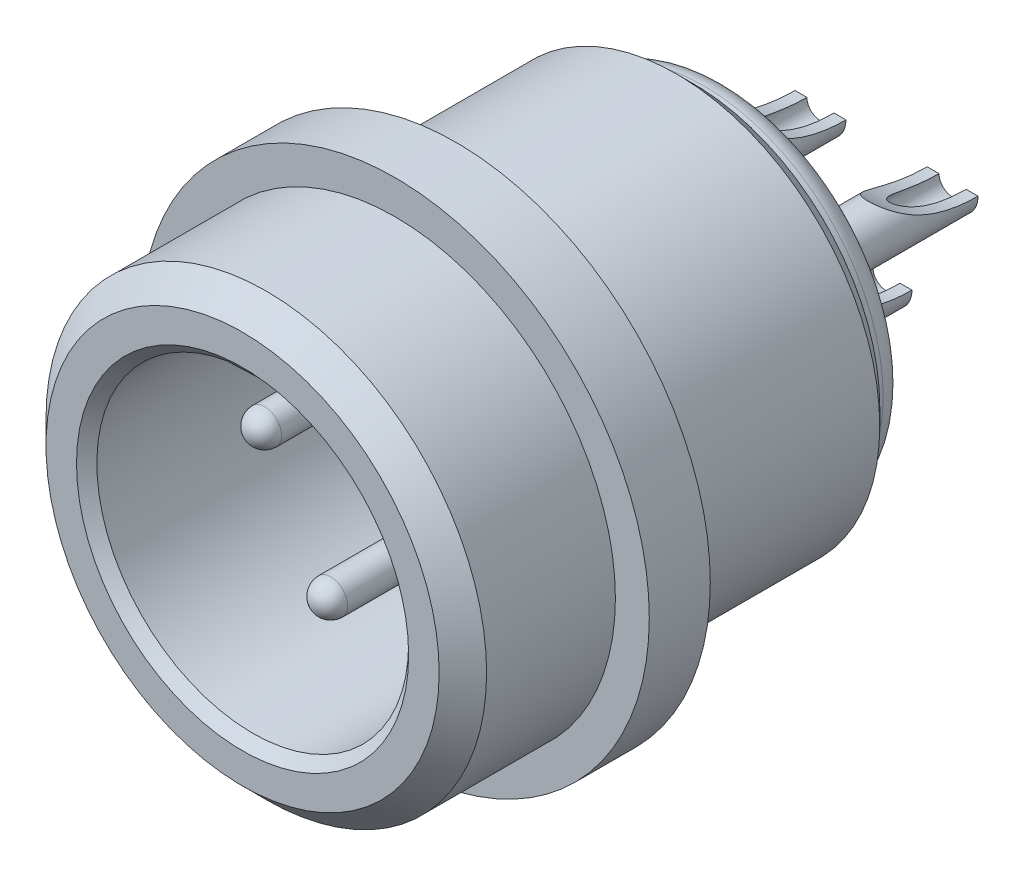
SolidWorks part; units mm, degrees
ref_plane "Спереди" through (0, 0, 0) normal (0, 0, 1) x (1, 0, 0)
ref_plane "Сверху" through (0, 0, 0) normal (0, 1, 0) x (1, 0, 0)
ref_plane "Справа" through (0, 0, 0) normal (1, 0, 0) x (0, 0, -1)
sketch "Эскиз1" plane through (0, 0, 0) normal (1, 0, 0) x (0, 0, -1)
  line L0 (0, 0) -> (112.3363, 0) construction
  line L1 (0, 4.6) -> (0, 5.8)
  line L2 (0.7, 6.5) -> (4.5, 6.5)
  line L3 (4.5, 6.5) -> (4.5, 7.5)
  line L4 (4.5, 7.5) -> (6.3, 7.5)
  line L5 (6.3, 7.5) -> (6.3, 6)
  line L6 (13.3, 5.3) -> (13.6, 5.3)
  line L7 (14.3, 4.6) -> (14.3, 4.5)
  line L8 (14.3, 4.5) -> (14, 4.5)
  line L9 (14, 4.5) -> (14, 0)
  line L10 (6.3, 6) -> (12.8, 6)
  line L11 (13.3, 5.5) -> (13.3, 5.3)
  line L12 (0, 4.6) -> (8.7, 4.6)
  line L13 (8.7, 4.6) -> (8.7, 0)
  line L14 (14, 0) -> (8.7, 0)
  line L15 (0, 5.8) -> (0.7, 6.5)
  line L16 (12.8, 6) -> (13.3, 5.5)
  arc A0 (14.3, 4.6) -> (13.6, 5.3) centre (13.6, 4.6) ccw
  point P4 (0, 6.5)
  point P15 (14.3, 5.3)
  point P19 (13.3, 6)
  dimension "D11" = 0.7
  dimension "D2" = 9.2
  dimension "D3" = 13
  dimension "D4" = 4.5
  dimension "D5" = 15
  dimension "D6" = 1.8
  dimension "D7" = 10.6
  dimension "D8" = 9
  dimension "D9" = 14.3
  dimension "D10" = 0.3
  dimension "D12" = 7
  dimension "D13" = 12
  dimension "D14" = 8.7
revolve "Повернуть1" add sketch "Эскиз1" angle 360 about L0
cosmetic thread "Условное изображение резьбы1" parameters "D2"=12
cosmetic thread "Условное изображение резьбы2" parameters "D2"=11
sketch "Эскиз2" plane through (0, 0, -8.7) normal (0, 0, 1) x (1, 0, 0)
  line L0 (-5.6904, 0) -> (5.786, 0) construction
  line L1 (0, 0) -> (0, -4.6) construction
  line L2 (0, 0) -> (1.9486, 1.125) construction
  line L3 (0, 0) -> (-1.9486, 1.125) construction
  circle A0 centre (1.9486, 1.125) radius 0.5
  circle A1 centre (0, -2.25) radius 0.5
  circle A2 centre (0, 0) radius 2.25 construction
  circle A3 centre (-1.9486, 1.125) radius 0.5
  circle A4 centre (0, 0) radius 4.6 construction
  circle A5 centre (0, 0) radius 4.6 construction
  dimension "D1" = 1
  dimension "D2" = 1
  dimension "D3" = 120
  dimension "D4" = 4.5
  dimension "D5" = 1
  dimension "D6" = 120
extrude "Вытянуть1" add sketch "Эскиз2" along normal offset from surface 2.1 and the other way blind 6 up to face at (4.6, 0, 0)
sketch "Эскиз8" plane through (0, 0, -8.7) normal (0, 0, 1) x (1, 0, 0)
  line L0 (0, 0) -> (0, 4.6) construction
  circle A1 centre (0, 4.6) radius 0.75
  circle A2 centre (0, 0) radius 4.6 construction
  dimension "D1" = 1.5
extrude "Бобышка-Вытянуть1" add sketch "Эскиз8" along normal up to surface (8.7 mm away) up to face at (4.6, 0, 0)
fillet "Скругление1" radius 0.5 3 edges at (-0.5, -2.25, -2.1) (1.4486, 1.125, -2.1) (-2.4486, 1.125, -2.1)
sketch "Эскиз10" plane through (0, 0, 0) normal (0, 1, 0) x (0, 0, -1)
  line L0 (0, 4.9) -> (2, 2.9)
  line L1 (2, 2.9) -> (0, 2.9)
  line L2 (0, 2.9) -> (0, 4.9)
  line L9 (0, 5.8) -> (0, -5.8) construction
  line L10 (0, 0) -> (2.4898, 0) construction
  point P5 (0, 0)
  dimension "D1" = 45
  dimension "D2" = 4.9
  dimension "D3" = 2
revolve "Вырез-Повернуть1" cut sketch "Эскиз10" angle 360 about L10
sketch "Эскиз7" plane through (0, 0, -14) normal (0, 0, -1) x (-1, 0, 0)
  line L0 (-1.2829, -0.952) -> (1.2157, -0.952) construction
  line L1 (1.2157, -1.8582) -> (3.412, -1.8582) construction
  line L2 (-3.6187, -1.8582) -> (-1.2829, -1.8582) construction
  text T0 "1" font "Arial Narrow" height in points 7
  text T1 "2" font "Arial Narrow" height in points 7
  text T2 "3" font "Arial Narrow" height in points 7
extrude "Вытянуть6" add sketch "Эскиз7" along normal blind 0.1
sketch "Эскиз11" plane through (0, 0, -14) normal (0, 0, -1) x (-1, 0, 0)
  circle A0 centre (-1.9486, 1.125) radius 0.75
  circle A1 centre (0, -2.25) radius 0.75
  circle A2 centre (1.9486, 1.125) radius 0.75
  dimension "D1" = 1.5
  dimension "D2" = 1.5
  dimension "D3" = 1.5
extrude "Бобышка-Вытянуть2" add sketch "Эскиз11" along normal blind 5
sketch "Эскиз12" plane through (0, 0, -19) normal (0, 0, -1) x (-1, 0, 0)
  circle A0 centre (-1.9486, 1.125) radius 0.4
  circle A1 centre (0, -2.25) radius 0.4
  circle A2 centre (1.9486, 1.125) radius 0.4
  dimension "D1" = 0.8
  dimension "D2" = 0.8
  dimension "D3" = 0.8
extrude "Вырез-Вытянуть1" cut sketch "Эскиз12" against normal up to surface (5 mm away) up to face at (0.75, -2.25, -14)
sketch "Эскиз14" plane through (0, 0, 0) normal (1, 0, 0) x (0, 0, -1)
  line L0 (19, 1.125) -> (16.2297, 1.125) construction
  line L1 (19, 0.375) -> (19, 1.875) construction
  line L2 (19, -2.25) -> (16.2297, -2.25) construction
  line L3 (19, -3) -> (19, -1.5) construction
  line L4 (19, 1.125) -> (19, 1.875)
  line L5 (19, 1.875) -> (16.5, 1.875)
  line L6 (19, 1.875) -> (14, 1.875) construction
  line L7 (19, -1.5) -> (16.5, -1.5)
  line L8 (19, -1.5) -> (14, -1.5) construction
  line L9 (19, -1.5) -> (19, -2.25)
  arc A0 (16.5, 1.875) -> (19, 1.125) centre (19, 5.6667) ccw
  arc A1 (16.5, -1.5) -> (19, -2.25) centre (19, 2.2917) ccw
  dimension "D1" = 2.5
  dimension "D2" = 2.5
extrude "Вырез-Вытянуть3" cut sketch "Эскиз14" against normal blind 4 and the other way blind 4
